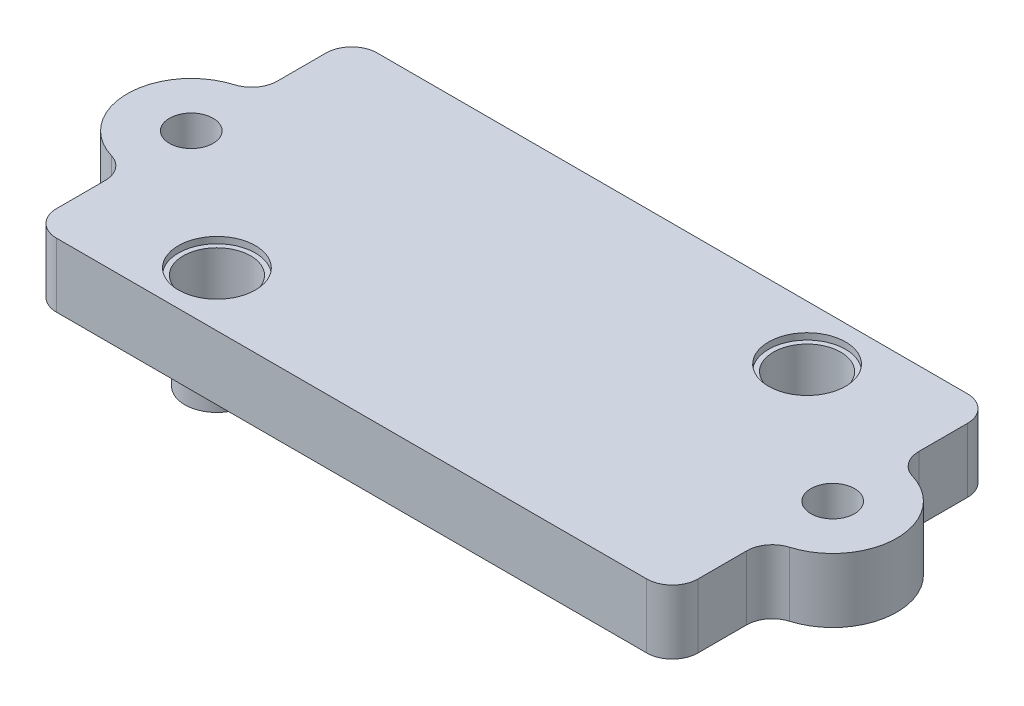
SolidWorks part; units mm, degrees
ref_plane "Front Plane" through (0, 0, 0) normal (0, 0, 1) x (1, 0, 0)
ref_plane "Top Plane" through (0, 0, 0) normal (0, 1, 0) x (1, 0, 0)
ref_plane "Right Plane" through (0, 0, 0) normal (1, 0, 0) x (0, 0, -1)
sketch "Sketch1" plane through (0, 0, 0) normal (0, 1, 0) x (1, 0, 0)
  line L0 (-25, 0) -> (25, 0) construction
  line L1 (-25, 12.5) -> (25, 12.5)
  line L2 (-25, 12.5) -> (-25, -12.5)
  line L3 (-25, -12.5) -> (25, -12.5)
  line L4 (25, 12.5) -> (25, -12.5)
  line L5 (-25, 12.5) -> (25, -12.5) construction
  line L6 (-25, -12.5) -> (25, 12.5) construction
  line L7 (-25, 5) -> (25, 5)
  line L8 (-25, -5) -> (25, -5)
  arc A0 (-25, 5) -> (-25, -5) centre (-25, 0) ccw
  arc A1 (25, -5) -> (25, 5) centre (25, 0) ccw
  circle A2 centre (-25, 0) radius 2.625
  circle A3 centre (25, 0) radius 2.625
  point P0 (0, 0)
  point P8 (0, 0)
  dimension "D3" = 5
  dimension "D4" = 5.25
  dimension "D1" = 25
  dimension "D2" = 50
extrude "Boss-Extrude1" add sketch "Sketch1" along normal blind 5 contours L8 L2 L3 L4 | A2 L2 A0 | A3 L4 L7 L2 A2 L8 | L2 L7 L4 L1 | A3 L4 A1 | L2 A2 | L4 A3 | L4 A3
fillet "Fillet1" radius 2 8 edges at (25, 2.5, 12.5) (-25, 2.5, 12.5) (-25, 2.5, 5) (-25, 2.5, -5) (-25, 2.5, -12.5) (25, 2.5, -12.5) (25, 2.5, -5) (25, 2.5, 5)
sketch "Sketch2" plane through (0, 0, 0) normal (0, -1, 0) x (1, 0, 0)
  line L0 (-14.75, 8.25) -> (14.75, -8.25) construction
  circle A0 centre (-14.75, 8.25) radius 2.5
  circle A1 centre (14.75, -8.25) radius 2.5
  point P12 (0, 0)
  dimension "D1" = 5
  dimension "D2" = 16.5
  dimension "D3" = 29.5
extrude "Boss-Extrude2" add sketch "Sketch2" along normal blind 3
sketch "Sketch5" plane through (0, 5, 0) normal (0, -1, 0) x (1, 0, 0)
  point P0 (-14.75, 8.25)
  point P1 (14.75, -8.25)
hole_wizard "CBORE for M3 SHCS1" positions "Sketch5" profile "Sketch6" counterbore size "M3" standard "ANSI Metric"
sketch "Sketch6" plane through (-14.75, 5, 8.25) normal (1, 0, 0) x (0, 0, 1)
  line L0 (0, 0) -> (0, 5.5773)
  line L1 (0, 5.5773) -> (2.625, 4)
  line L2 (2.625, 4) -> (2.625, 0.5)
  line L3 (2.625, 0.5) -> (3, 0.5)
  line L4 (3, 0.5) -> (3, 0)
  line L5 (3, 0) -> (0, 0)
  line L10 (0, 5.5773) -> (-2.625, 4) construction
  line L11 (0, -6.35) -> (0, 107.95) construction
  dimension "Hole Dia." = 5.25
  dimension "Hole Depth" = 4
  dimension "C'Bore Dia." = 6
  dimension "C'Bore Depth" = 0.5
  dimension "Drill Angle" = 118
sketch "Sketch8" plane through (0, 0, 0) normal (0, -1, 0) x (1, 0, 0)
  line L0 (25, -12.5) -> (25, 12.5) construction
  point P0 (-25, 0)
  point P1 (25, 0)
hole_wizard "CSK for M3 Flat Head Machine Screw1" positions "Sketch8" profile "Sketch9" countersink size "M3" standard "ANSI Metric" end condition through all
sketch "Sketch9" plane through (-25, 0, 0) normal (1, 0, 0) x (0, 0, -1)
  line L0 (0, 0) -> (0, 5)
  line L1 (0, 5) -> (1.7, 5)
  line L2 (1.7, 5) -> (1.7, 1.45)
  line L3 (1.7, 1.45) -> (3.15, 0)
  line L5 (3.15, 0) -> (0, 0)
  line L6 (-1.7, 1.45) -> (-3.15, 0) construction
  line L11 (0, -6.35) -> (0, 107.95) construction
  dimension "Thru Hole Dia." = 3.4
  dimension "Thru Hole Depth" = 5
  dimension "Near C'Sink Dia." = 6.3
  dimension "Near C'Sink Angle" = 90
sketch "Sketch10" plane through (0, -3, 0) normal (0, -1, 0) x (1, 0, 0)
  point P0 (-14.75, 8.25)
  point P1 (14.75, -8.25)
hole_wizard "M3 Clearance Hole1" positions "Sketch10" profile "Sketch11" hole size "M3" standard "ANSI Metric"
sketch "Sketch11" plane through (-14.75, -3, 8.25) normal (1, 0, 0) x (0, 0, -1)
  line L0 (0, 0) -> (0, 4.9764)
  line L1 (0, 4.9764) -> (1.625, 4)
  line L2 (1.625, 4) -> (1.625, 0)
  line L5 (1.625, 0) -> (0, 0)
  line L10 (0, 4.9764) -> (-1.625, 4) construction
  line L11 (0, -6.35) -> (0, 107.95) construction
  dimension "Hole Dia." = 3.25
  dimension "Hole Depth" = 4
  dimension "Drill Angle" = 118
